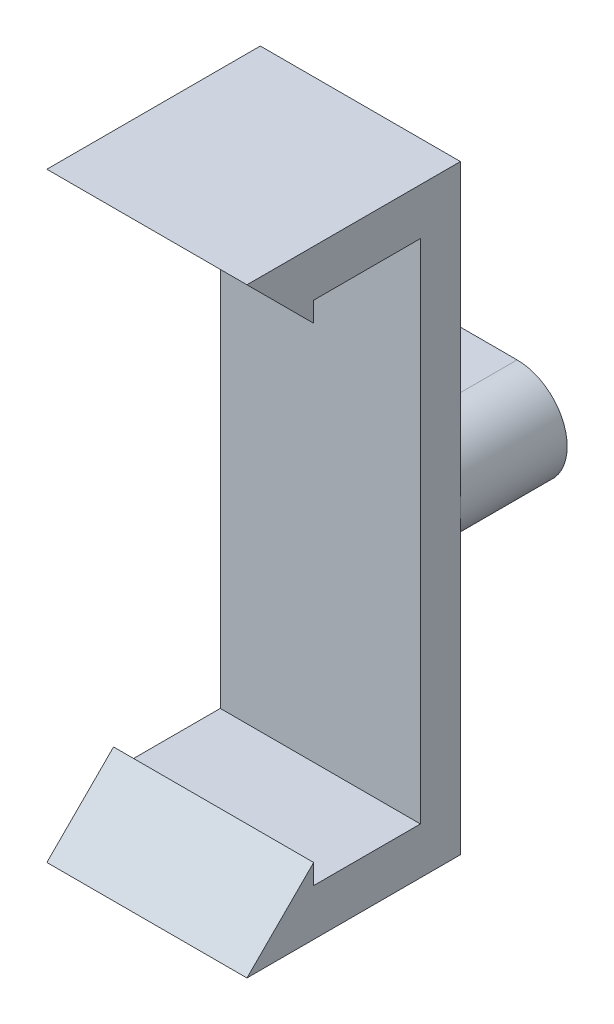
SolidWorks part; units mm, degrees
ref_plane "Ön Düzlem" through (0, 0, 0) normal (0, 0, 1) x (1, 0, 0)
ref_plane "Üst Düzlem" through (0, 0, 0) normal (0, 1, 0) x (1, 0, 0)
ref_plane "Sağ Düzlem" through (0, 0, 0) normal (1, 0, 0) x (0, 0, -1)
sketch "Çizim2" plane through (0, 0, 0) normal (0, 0, 1) x (1, 0, 0)
  line L1 (-3, 9) -> (3, 9)
  line L2 (-3, 9) -> (-3, -9)
  line L3 (-3, -9) -> (3, -9)
  line L4 (3, 9) -> (3, -9)
  line L5 (-3, 9) -> (3, -9) construction
  line L6 (-3, -9) -> (3, 9) construction
  point P0 (0, 0)
  point P6 (0, 9)
  dimension "D1" = 6
  dimension "D2" = 18
extrude "Yükseklik-Ekstrüzyon1" add sketch "Çizim2" along normal blind 1.2
sketch "Çizim3" plane through (0, 0, 1.2) normal (0, 0, 1) x (1, 0, 0)
  line L0 (3, -9) -> (3, 9) construction
  line L1 (-3, 9) -> (3, 9)
  line L2 (-3, 9) -> (-3, 7.6)
  line L3 (-3, 7.6) -> (3, 7.6)
  line L4 (3, 9) -> (3, 7.6)
  line L5 (-3, 0) -> (3, 0) construction
  line L6 (-3, 9) -> (-3, -9) construction
  line L7 (-3, -7.6) -> (3, -7.6)
  line L8 (3, -9) -> (3, -7.6)
  line L9 (-3, -9) -> (3, -9)
  line L10 (-3, -9) -> (-3, -7.6)
  dimension "D1" = 1.4
extrude "Yükseklik-Ekstrüzyon4" add sketch "Çizim3" along normal blind 3.2
sketch "Çizim6" plane through (0, 0, 4.4) normal (0, 0, 1) x (1, 0, 0)
  line L1 (-3, 9) -> (3, 9)
  line L2 (-3, 9) -> (-3, 7)
  line L3 (-3, 7) -> (3, 7)
  line L4 (3, 9) -> (3, 7)
  dimension "D1" = 6
  dimension "D2" = 2
extrude "Yükseklik-Ekstrüzyon5" add sketch "Çizim6" along normal blind 2
sketch "Çizim7" plane through (3, 0, 0) normal (1, 0, 0) x (0, 0, -1)
  line L0 (-6.4, 9) -> (-4.4, 7)
  line L1 (-4.4, 7) -> (-6.4, 7)
  line L2 (-6.4, 7) -> (-6.4, 9)
extrude "Kes-Ekstrüzyon2" cut sketch "Çizim7" against normal blind 6
sketch "Çizim8" plane through (0, 0, 4.4) normal (0, 0, 1) x (1, 0, 0)
  line L1 (-3, -9) -> (3, -9)
  line L2 (-3, -9) -> (-3, -7)
  line L3 (-3, -7) -> (3, -7)
  line L4 (3, -9) -> (3, -7)
  dimension "D1" = 6
  dimension "D2" = 2
extrude "Yükseklik-Ekstrüzyon6" add sketch "Çizim8" along normal blind 2
sketch "Çizim9" plane through (-3, 0, 0) normal (-1, 0, 0) x (0, 0, 1)
  line L0 (6.4, -9) -> (4.4, -7)
  line L1 (4.4, -7) -> (6.4, -7)
  line L2 (6.4, -7) -> (6.4, -9)
extrude "Kes-Ekstrüzyon3" cut sketch "Çizim9" against normal blind 6
sketch "Çizim10" plane through (0, 0, 0) normal (0, 0, -1) x (-1, 0, 0)
  line L0 (3, 0) -> (-3, 0) construction
  line L1 (3, 9) -> (3, -9) construction
  line L2 (-3, -9) -> (-3, 9) construction
  line L3 (0, 9) -> (0, -9) construction
  line L4 (-3, 9) -> (3, 9) construction
  line L5 (3, -9) -> (-3, -9) construction
  line L6 (1.5, 1.5) -> (-1.5, 1.5)
  line L7 (1.5, -1.5) -> (-1.5, -1.5)
  arc A0 (1.5, -1.5) -> (1.5, 1.5) centre (1.5, 0) ccw
  arc A1 (-1.5, -1.5) -> (-1.5, 1.5) centre (-1.5, 0) cw
  dimension "D1" = 3
  dimension "D2" = 1.5
extrude "Yükseklik-Ekstrüzyon8" add sketch "Çizim10" along normal blind 3.2
sketch "Çizim12" plane through (0, 0, -3.2) normal (0, 0, -1) x (-1, 0, 0)
  circle A0 centre (0, 0) radius 0.75
  dimension "D1" = 1.5
extrude "Kes-Ekstrüzyon4" cut sketch "Çizim12" against normal blind 4
